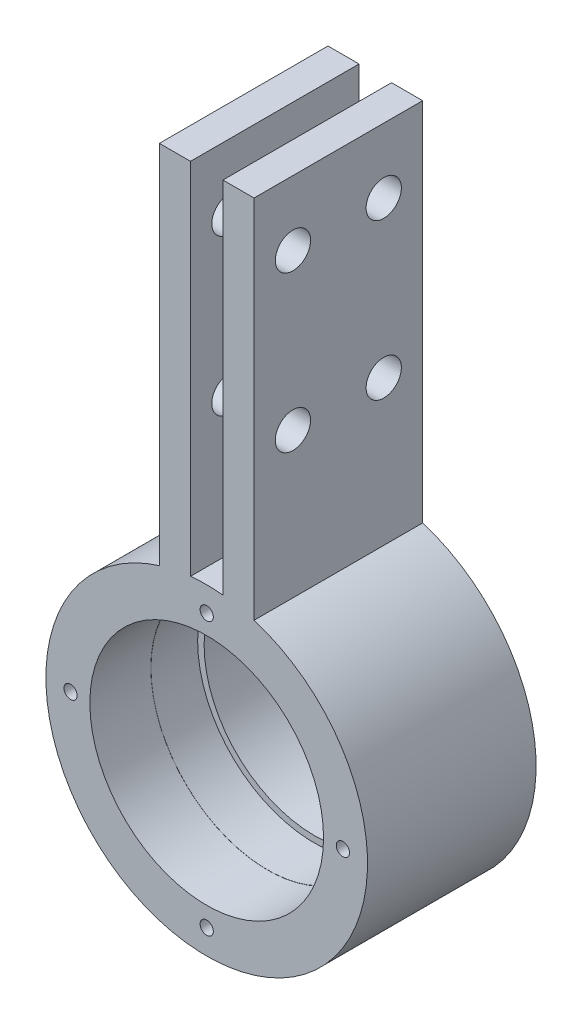
SolidWorks part; units mm, degrees
ref_plane "Front Plane" through (0, 0, 0) normal (0, 0, 1) x (1, 0, 0)
ref_plane "Top Plane" through (0, 0, 0) normal (0, 1, 0) x (1, 0, 0)
ref_plane "Right Plane" through (0, 0, 0) normal (1, 0, 0) x (0, 0, -1)
sketch "Sketch1" plane through (0, 0, 0) normal (0, 0, 1) x (1, 0, 0)
  line L0 (6.25, 200.2532) -> (18.25, 200.2532)
  line L2 (-18.25, 59.2532) -> (-18.25, 200.2532)
  line L3 (-18.25, 200.2532) -> (-6.25, 200.2532)
  line L4 (18.25, 59.2532) -> (18.25, 200.2532)
  line L5 (-18.25, 59.2532) -> (-6.25, 105.6093) construction
  line L6 (-18.25, 200.2532) -> (-6.25, 153.897) construction
  line L7 (-18.25, 200.2532) -> (-6.25, 200.2532)
  line L8 (-18.25, 200.2532) -> (-18.25, 59.2532)
  line L10 (-6.25, 200.2532) -> (-6.25, 61.6842)
  line L11 (18.25, 200.2532) -> (6.25, 200.2532)
  line L12 (18.25, 200.2532) -> (18.25, 59.2532)
  line L14 (6.25, 200.2532) -> (6.25, 61.6842)
  line L15 (6.25, 153.897) -> (18.25, 200.2532) construction
  line L16 (6.25, 105.6093) -> (18.25, 59.2532) construction
  circle A0 centre (0, 0) radius 42.5
  arc A1 (-18.25, 59.2532) -> (18.25, 59.2532) centre (0, 0) ccw
  arc A2 (6.25, 61.6842) -> (-6.25, 61.6842) centre (0, 0) ccw
  point P4 (0, 129.7532)
  point P13 (0, 0)
  point P18 (0, 0)
  point P19 (0, 0)
  dimension "D5" = 124
  dimension "D6" = 85
  dimension "D1" = 12
  dimension "D2" = 12
  dimension "D3" = 12.5
  dimension "D4" = 141
extrude "Boss-Extrude1" add sketch "Sketch1" along normal blind 65 contours L14 A2 L10 L3 L2 A1 L4 L0 A0
sketch "Sketch2" plane through (0, 0, 65) normal (0, 0, 1) x (1, 0, 0)
  circle A0 centre (0, 0) radius 45.05
  dimension "D1" = 90.1
extrude "Cut-Extrude1" cut sketch "Sketch2" against normal blind 23.5
sketch "Sketch3" plane through (0, 0, 41.5) normal (0, 0, 1) x (1, 0, 0)
  circle A0 centre (0, 0) radius 44.9925
  dimension "D1" = 89.985
extrude "Cut-Extrude2" cut sketch "Sketch3" against normal blind 18
hole_wizard "M6 Tapped Hole1" positions "Sketch4" profile "Sketch5" tap size "M6" standard "ISO"
sketch "Sketch4" plane through (0, 0, 65) normal (0, 0, 1) x (1, 0, 0)
  circle A1 centre (0, 0) radius 52.5 construction
  point P13 (-52.5, 0)
  point P15 (0, 52.5)
  point P17 (52.5, 0)
  point P19 (0, -52.5)
  dimension "D1" = 105
sketch "Sketch5" plane through (0, -52.5, 65) normal (1, 0, 0) x (0, -1, 0)
  line L0 (0, 0) -> (0, 13.5322)
  line L1 (0, 13.5322) -> (2.55, 12)
  line L2 (2.55, 12) -> (2.55, 0)
  line L5 (2.55, 0) -> (0, 0)
  line L10 (0, 13.5322) -> (-2.55, 12) construction
  line L11 (0, -6.35) -> (0, 107.95) construction
  dimension "Tap Drill Dia." = 5.1
  dimension "Tap Drill Depth" = 12
  dimension "Drill Angle" = 118
cosmetic thread "Hole Thread1" parameters "D1"=12, "D2"=6
cosmetic thread "Hole Thread2" parameters "D1"=12, "D2"=6
cosmetic thread "Hole Thread3" parameters "D1"=12, "D2"=6
cosmetic thread "Hole Thread4" parameters "D1"=12, "D2"=6
hole_wizard "M6 Tapped Hole2" positions "Sketch7" profile "Sketch8" tap size "M6" standard "ISO"
sketch "Sketch7" plane through (0, 0, 0) normal (0, 0, -1) x (-1, 0, 0)
  circle A0 centre (0, 0) radius 52.5
  point P7 (0, 52.5)
  point P9 (52.5, 0)
  point P11 (0, -52.5)
  point P15 (-52.5, 0)
  dimension "D1" = 105
sketch "Sketch8" plane through (52.5, 0, 0) normal (1, 0, 0) x (0, 1, 0)
  line L0 (0, 0) -> (0, 13.5322)
  line L1 (0, 13.5322) -> (2.55, 12)
  line L2 (2.55, 12) -> (2.55, 0)
  line L5 (2.55, 0) -> (0, 0)
  line L10 (0, 13.5322) -> (-2.55, 12) construction
  line L11 (0, -6.35) -> (0, 107.95) construction
  dimension "Tap Drill Dia." = 5.1
  dimension "Tap Drill Depth" = 12
  dimension "Drill Angle" = 118
cosmetic thread "Hole Thread5" parameters "D1"=12, "D2"=6
cosmetic thread "Hole Thread6" parameters "D1"=12, "D2"=6
cosmetic thread "Hole Thread7" parameters "D1"=12, "D2"=6
cosmetic thread "Hole Thread8" parameters "D1"=12, "D2"=6
hole_wizard "Ø12.0mm Dowel Hole1" positions "Sketch10" profile "Sketch11" hole size "Ø12.0" standard "ISO" end condition through all
sketch "Sketch10" plane through (18.25, 0, 0) normal (1, 0, 0) x (0, 0, -1)
  line L0 (-65, 200.2532) -> (0, 200.2532) construction
  line L1 (0, 59.2532) -> (0, 200.2532) construction
  line L2 (-65, 59.2532) -> (-65, 200.2532) construction
  point P0 (-50, 175.2532)
  point P2 (-15, 175.2532)
  point P4 (-15, 115.2532)
  point P6 (-50, 115.2532)
  point P9 (0, 0)
  point P10 (0, 0)
  point P11 (0, 0)
  point P12 (0, 0)
  dimension "D1" = 25
  dimension "D2" = 15
  dimension "D3" = 15
  dimension "D4" = 60
sketch "Sketch11" plane through (18.25, 175.2532, 50) normal (0, 1, 0) x (0, 0, -1)
  line L0 (0, 0) -> (0, 80.25)
  line L1 (0, 80.25) -> (6.8, 80.25)
  line L2 (6.8, 80.25) -> (6.8, 0)
  line L5 (6.8, 0) -> (0, 0)
  line L11 (0, -6.35) -> (0, 107.95) construction
  dimension "Thru Hole Dia." = 13.6
  dimension "Thru Hole Depth" = 80.25
